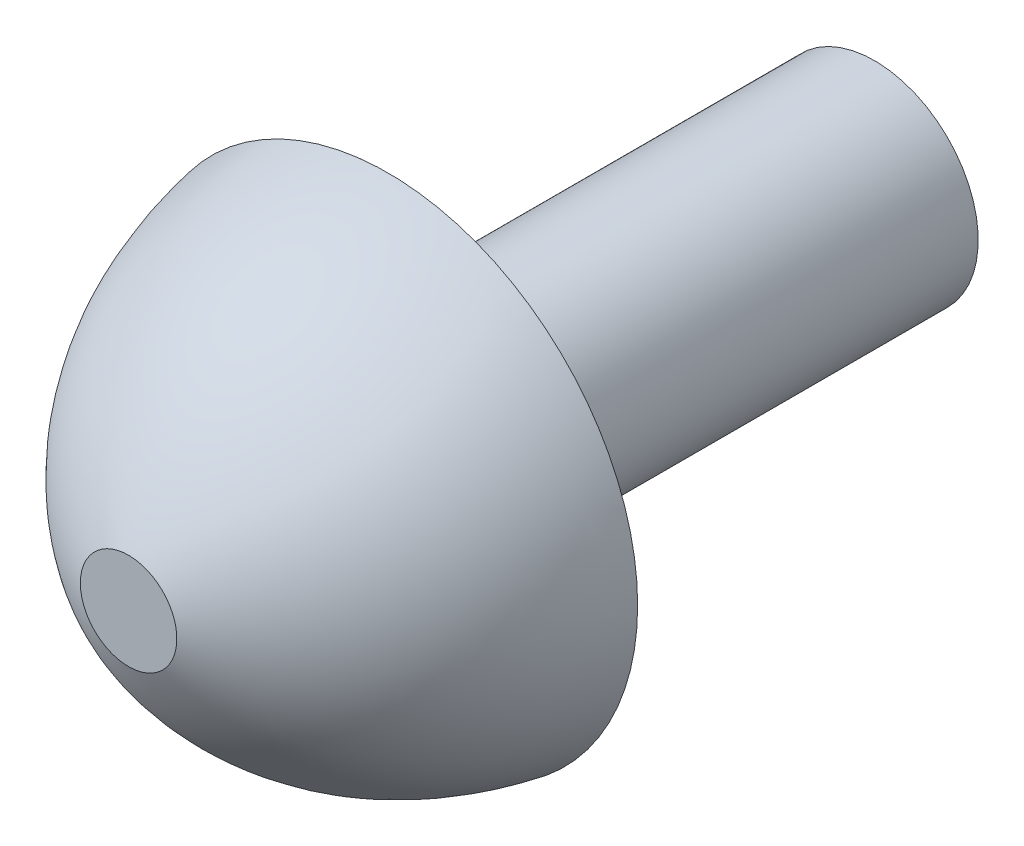
SolidWorks part; units mm, degrees
ref_plane "前视基准面" through (0, 0, 0) normal (0, 0, 1) x (1, 0, 0)
ref_plane "上视基准面" through (0, 0, 0) normal (0, 1, 0) x (1, 0, 0)
ref_plane "右视基准面" through (0, 0, 0) normal (1, 0, 0) x (0, 0, -1)
sketch "草图1" plane through (0, 0, 0) normal (0, 1, 0) x (1, 0, 0)
  line L0 (-4.1425, -3.8038) -> (3.3575, -3.8038)
  line L1 (-7.1425, 11.1962) -> (-1.1425, 11.1962)
  line L2 (-7.1425, 11.1962) -> (-7.1425, -3.8038)
  line L3 (-7.1425, -3.8038) -> (-1.1425, -3.8038)
  line L4 (-1.1425, 11.1962) -> (-1.1425, -3.8038)
  line L6 (-2.8514, -11.8038) -> (-4.7501, -11.8038)
  line L7 (-4.7501, -11.8038) -> (-4.7501, -3.8038)
  line L8 (-4.3387, 16.2975) -> (-4.3387, -21.5506) construction
  spline S0 degree 2 poles (3.3575, -3.8038) (2.344, -9.4189) (-2.8514, -11.8038) knots 0 0 0 1 1 1
  dimension "D1" = 15
  dimension "D2" = 6
  dimension "D3" = 8
  dimension "D4" = 7.5
revolve "旋转2" add sketch "草图1" angle 360 about L8
